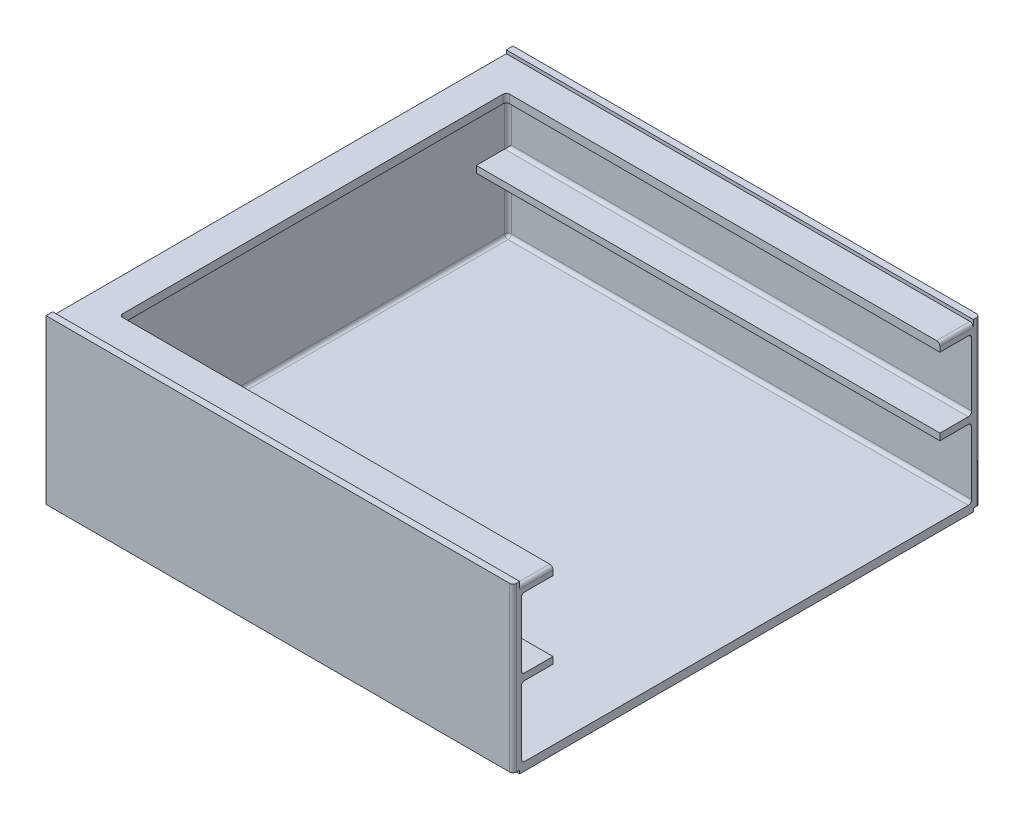
SolidWorks part; units mm, degrees
ref_plane "前视基准面" through (0, 0, 0) normal (0, 0, 1) x (1, 0, 0)
ref_plane "上视基准面" through (0, 0, 0) normal (0, 1, 0) x (1, 0, 0)
ref_plane "右视基准面" through (0, 0, 0) normal (1, 0, 0) x (0, 0, -1)
sketch "草图1" plane through (0, 0, 0) normal (0, 1, 0) x (1, 0, 0)
  line L1 (140, -140) -> (-140, -140)
  line L2 (140, -140) -> (140, 140)
  line L3 (140, 140) -> (-140, 140)
  line L4 (-140, -140) -> (-140, 140)
  line L5 (140, -140) -> (-140, 140) construction
  line L6 (140, 140) -> (-140, -140) construction
  point P0 (0, 0)
  dimension "D1" = 280
  dimension "D2" = 280
extrude "凸台-拉伸1" add sketch "草图1" along normal blind 100
sketch "草图2" plane through (0, 100, 0) normal (0, 1, 0) x (1, 0, 0)
  line L0 (140, -140) -> (140, 140) construction
  line L1 (140, 140) -> (-140, 140) construction
  line L5 (140, -136) -> (-140, -136)
  line L6 (140, -136) -> (140, 136)
  line L7 (140, 136) -> (-140, 136)
  line L8 (-140, -136) -> (-140, 136)
  line L9 (140, -136) -> (-140, 136) construction
  line L10 (140, 136) -> (-140, -136) construction
  point P0 (0, 0)
  dimension "D1" = 0
  dimension "D2" = 4
extrude "切除-拉伸1" cut sketch "草图2" against normal blind 2
sketch "草图3" plane through (0, 0, 0) normal (0, -1, 0) x (1, 0, 0)
  line L0 (-140, 136) -> (140, 136)
  line L1 (-140, -140) -> (-140, 140) construction
  line L2 (140, 140) -> (140, -140) construction
  line L3 (140, -140) -> (-140, -140) construction
  line L4 (-140, 140) -> (140, 140) construction
  line L5 (140, -140) -> (-140, -140)
  line L6 (140, 140) -> (140, 136)
  line L7 (-140, 140) -> (140, 140)
  line L8 (-140, -140) -> (-140, -136)
  line L9 (-140, -136) -> (140, -136)
  line L10 (-140, 136) -> (-140, 140)
  line L11 (140, -136) -> (140, -140)
  dimension "D1" = 4
  dimension "D2" = 4
extrude "切除-拉伸2" cut sketch "草图3" against normal blind 2
sketch "草图4" plane through (140, 0, 0) normal (1, 0, 0) x (0, 0, -1)
  line L0 (0, 98) -> (0, 0) construction
  line L1 (-136, 98) -> (136, 98) construction
  line L2 (-136, 0) -> (136, 0) construction
  line L6 (140, 100) -> (140, 2) construction
  line L7 (135, 5) -> (-135, 5)
  line L8 (135, 5) -> (135, 93)
  line L9 (135, 93) -> (-135, 93)
  line L10 (-135, 5) -> (-135, 93)
  line L11 (135, 5) -> (-135, 93) construction
  line L12 (135, 93) -> (-135, 5) construction
  point P6 (0, 49)
  point P8 (0, 49)
  dimension "D1" = 5
  dimension "D2" = 5
extrude "切除-拉伸3" cut sketch "草图4" against normal offset from surface (278 mm away) 2 up to face at (-140, 50.3333, 0)
sketch "草图6" plane through (0, 98, 0) normal (0, 1, 0) x (1, 0, 0)
  line L11 (140, -136) -> (140, 136) construction
  line L12 (140, 116) -> (-120, 116)
  line L14 (140, 116) -> (140, -116)
  line L15 (140, -116) -> (-120, -116)
  line L16 (-120, 116) -> (-120, -116)
  line L17 (140, 136) -> (-140, 136) construction
  line L18 (-140, -136) -> (140, -136) construction
  line L19 (-140, 136) -> (-140, -136) construction
  dimension "D1" = 20
  dimension "D2" = 20
  dimension "D3" = 20
extrude "切除-拉伸7" cut sketch "草图6" against normal up to surface (93 mm away) up to face at (1, 5, 0)
sketch "草图7" plane through (0, 0, 0) normal (1, 0, 0) x (0, 0, -1)
  line L0 (-135, 93) -> (-135, 5) construction
  line L1 (-135, 93) -> (-135, 89)
  line L2 (-135, 49) -> (135, 49) construction
  line L3 (135, 93) -> (135, 5) construction
  line L4 (0, 93) -> (0, 5) construction
  line L5 (-135, 93) -> (135, 93) construction
  line L6 (135, 5) -> (-135, 5) construction
  line L7 (-135, 93) -> (-134, 93)
  line L8 (-134, 93) -> (-134, 89)
  line L9 (-134, 89) -> (-135, 89)
  line L10 (-134, 9) -> (-135, 9)
  line L11 (-134, 5) -> (-134, 9)
  line L12 (-135, 5) -> (-134, 5)
  line L13 (-135, 5) -> (-135, 9)
  line L14 (135, 5) -> (135, 9)
  line L15 (135, 5) -> (134, 5)
  line L16 (134, 5) -> (134, 9)
  line L17 (134, 9) -> (135, 9)
  line L18 (134, 89) -> (135, 89)
  line L19 (134, 93) -> (134, 89)
  line L20 (135, 93) -> (134, 93)
  line L21 (135, 93) -> (135, 89)
  dimension "D1" = 1
  dimension "D2" = 4
  dimension "D3" = 40
fillet "圆角4" radius 2 2 edges at (140, 51, -140) (140, 51, 140)
fillet "圆角5" radius 2 2 edges at (140, 98, -126) (140, 98, 126)
fillet "圆角6" radius 2 2 edges at (-120, 95.5, 116) (-120, 95.5, -116)
sketch "草图8" plane through (-138, 0, 0) normal (1, 0, 0) x (0, 0, -1)
  line L0 (0, 93) -> (0, 5) construction
  line L1 (-135, 49) -> (135, 49) construction
  line L2 (-135, 5) -> (-135, 93) construction
  line L3 (-135, 47) -> (-135, 51)
  line L4 (-135, 51) -> (-116, 51)
  line L5 (-116, 51) -> (-116, 47)
  line L6 (135, 5) -> (135, 93) construction
  line L7 (135, 47) -> (135, 51)
  line L8 (116, 51) -> (116, 47)
  line L9 (135, 51) -> (116, 51)
  line L10 (135, 47) -> (116, 47)
  line L11 (-135, 47) -> (-116, 47)
  point P19 (116, 49)
  point P21 (-116, 49)
  dimension "D1" = 19
  dimension "D2" = 4
extrude "凸台-拉伸2" add sketch "草图8" along normal up to surface (278 mm away) up to face at (140, 58.7, 0)
fillet "圆角7" radius 2 14 edges at (-138, 26, -135) (1, 5, -135) (1, 47, -135) (1, 51, -135) (1, 93, -135) (1, 5, 135) (1, 47, 135) (-138, 26, 135) (1, 51, 135) (1, 93, 135) (-138, 93, 0) (-138, 72, 135) (-138, 72, -135) (-138, 5, 0)
